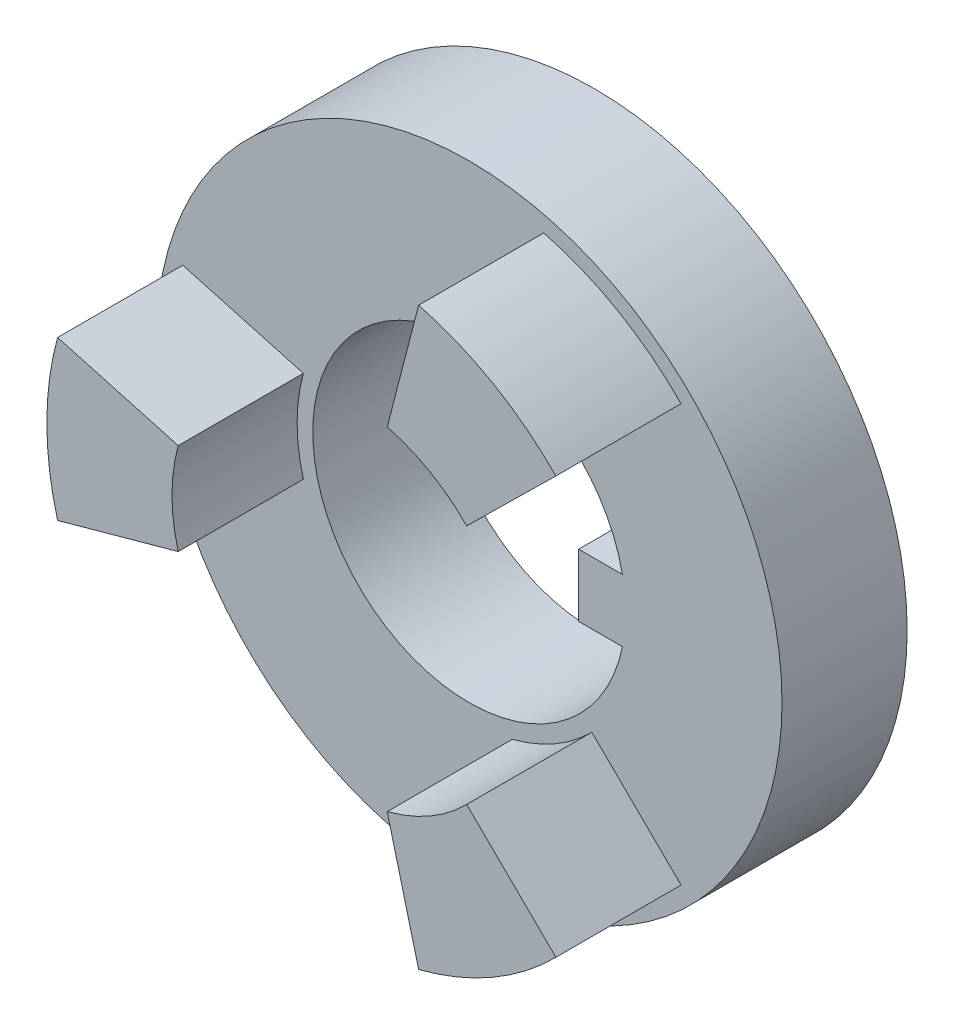
SolidWorks part; units mm, degrees
ref_plane "Front Plane" through (0, 0, 0) normal (0, 0, 1) x (1, 0, 0)
ref_plane "Top Plane" through (0, 0, 0) normal (0, 1, 0) x (1, 0, 0)
ref_plane "Right Plane" through (0, 0, 0) normal (1, 0, 0) x (0, 0, -1)
sketch "Sketch1" plane through (0, 0, 0) normal (0, 0, 1) x (1, 0, 0)
  circle A0 centre (0, 0) radius 10
  circle A1 centre (0, 0) radius 5
  dimension "D1" = 20
  dimension "D2" = 10
extrude "Boss-Extrude2" add sketch "Sketch1" along normal blind 4
sketch "Sketch2" plane through (0, 0, 4) normal (0, 0, 1) x (1, 0, 0)
  line L0 (-10, 0) -> (-9.5, 0)
  line L1 (-5.3008, 1.4667) -> (-9.156, 2.5333)
  line L2 (-5.3008, -1.4667) -> (-9.156, -2.5333)
  line L3 (-5.5, 0) -> (-5, 0)
  line L4 (3.9206, 3.8573) -> (6.7719, 6.6627)
  line L5 (1.3802, 5.324) -> (2.3841, 9.196)
  line L6 (1.3802, -5.324) -> (2.3841, -9.196)
  line L7 (3.9206, -3.8573) -> (6.7719, -6.6627)
  circle A0 centre (0, 0) radius 10 construction
  circle A1 centre (0, 0) radius 5 construction
  circle A3 centre (0, 0) radius 9.5
  circle A4 centre (0, 0) radius 5.5
  point P27 (0, 0)
  dimension "D1" = 3
extrude "Boss-Extrude3" add sketch "Sketch2" along normal blind 4 contours A4 L1 A3 L2 | A4 L6 A3 L7 | A4 L4 A3 L5
ref_plane "Plane1" through (4.578, 7.9293, 0) normal (0.5, 0.866, 0) x (0.866, -0.5, 0)
sketch "Sketch3" plane through (0, 0, 0) normal (0, 0, -1) x (-1, 0, 0)
  line L1 (-6.5, 1) -> (-3.5, 1)
  line L2 (-6.5, 1) -> (-6.5, -1)
  line L3 (-6.5, -1) -> (-3.5, -1)
  line L4 (-3.5, 1) -> (-3.5, -1)
  line L5 (-6.5, 1) -> (-3.5, -1) construction
  line L6 (-6.5, -1) -> (-3.5, 1) construction
  circle A0 centre (0, 0) radius 5 construction
  point P0 (-5, 0)
  dimension "D1" = 3
  dimension "D2" = 2
extrude "Boss-Extrude4" add sketch "Sketch3" against normal blind 4
